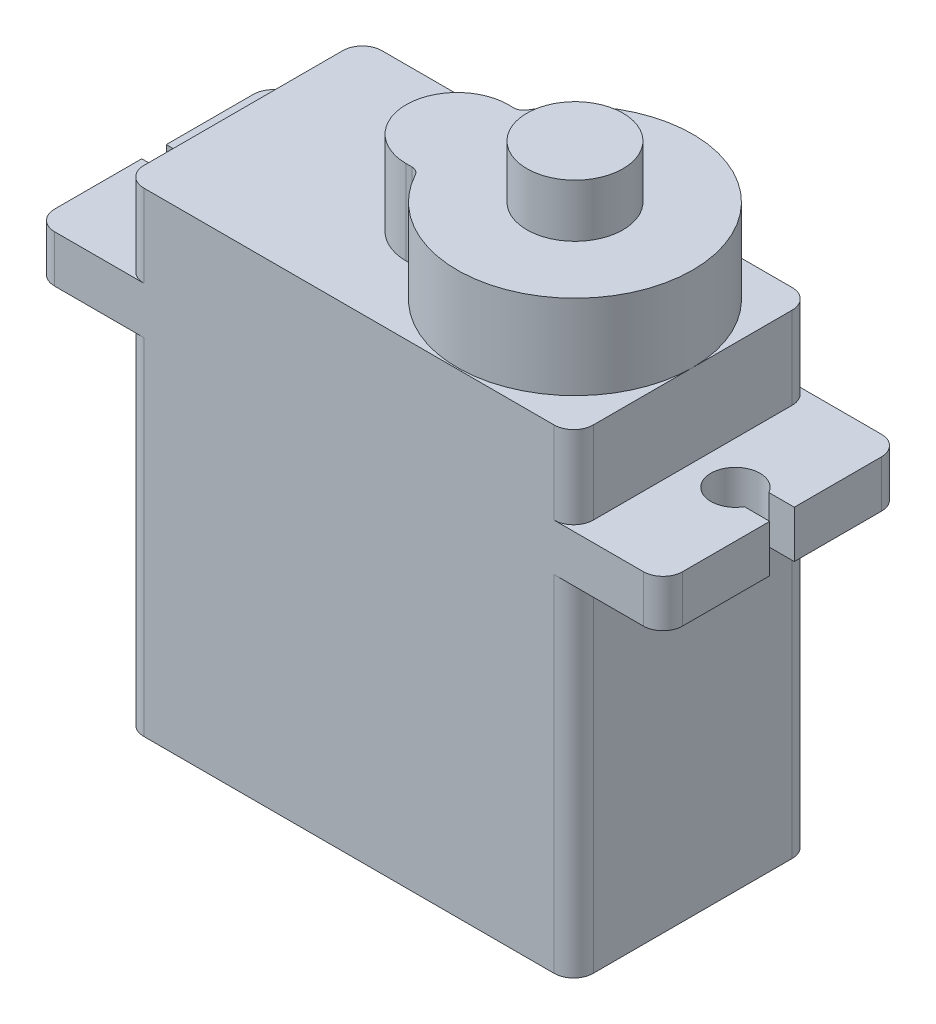
SolidWorks part; units mm, degrees
ref_plane "Plano frontal" through (0, 0, 0) normal (0, 0, 1) x (1, 0, 0)
ref_plane "Plano superior" through (0, 0, 0) normal (0, 1, 0) x (1, 0, 0)
ref_plane "Plano direito" through (0, 0, 0) normal (1, 0, 0) x (0, 0, -1)
sketch "Esboço2" plane through (0, 0, 0) normal (0, 1, 0) x (1, 0, 0)
  line L1 (11.45, 6.065) -> (-11.45, 6.065)
  line L2 (11.45, 6.065) -> (11.45, -6.065)
  line L3 (11.45, -6.065) -> (-11.45, -6.065)
  line L4 (-11.45, 6.065) -> (-11.45, -6.065)
  line L5 (11.45, 6.065) -> (-11.45, -6.065) construction
  line L6 (11.45, -6.065) -> (-11.45, 6.065) construction
  point P0 (0, 0)
  dimension "D1" = 22.9
  dimension "D2" = 12.13
extrude "Ressalto-extrusão1" add sketch "Esboço2" along normal blind 17.35
sketch "Esboço3" plane through (0, 17.35, 0) normal (0, 1, 0) x (1, 0, 0)
  line L1 (16, -6.065) -> (-16, -6.065)
  line L2 (16, -6.065) -> (16, 6.065)
  line L3 (16, 6.065) -> (-16, 6.065)
  line L4 (-16, -6.065) -> (-16, 6.065)
  line L5 (16, -6.065) -> (-16, 6.065) construction
  line L6 (16, 6.065) -> (-16, -6.065) construction
  line L7 (-11.45, -6.065) -> (11.45, -6.065) construction
  point P0 (0, 0)
  dimension "D1" = 32
  dimension "D2" = 0
extrude "Ressalto-extrusão2" add sketch "Esboço3" along normal blind 2.4
sketch "Esboço4" plane through (0, 19.75, 0) normal (0, 1, 0) x (1, 0, 0)
  line L1 (-11.45, -6.065) -> (11.45, -6.065)
  line L2 (-11.45, -6.065) -> (-11.45, 6.065)
  line L3 (-11.45, 6.065) -> (11.45, 6.065)
  line L4 (11.45, -6.065) -> (11.45, 6.065)
extrude "Ressalto-extrusão3" add sketch "Esboço4" along normal blind 4.45
sketch "Esboço5" plane through (0, 19.75, 0) normal (0, 1, 0) x (1, 0, 0)
  line L0 (0, -6.065) -> (0, 6.065) construction
  line L1 (-11.45, -6.065) -> (11.45, -6.065) construction
  line L2 (11.45, 6.065) -> (-11.45, 6.065) construction
  line L3 (-16, -0.625) -> (-16, 0.625)
  line L4 (-14.7075, 0.625) -> (-16, 0.625)
  line L5 (-14.7075, -0.625) -> (-16, -0.625)
  line L18 (14.7075, -0.625) -> (16, -0.625)
  line L19 (14.7075, 0.625) -> (16, 0.625)
  line L26 (16, -0.625) -> (16, 0.625)
  arc A0 (14.7075, 0.625) -> (14.7075, -0.625) centre (13.625, 0) ccw
  arc A1 (-14.7075, 0.625) -> (-14.7075, -0.625) centre (-13.625, 0) cw
  dimension "D2" = 2.5
extrude "Corte-extrusão1" cut sketch "Esboço5" against normal blind 2.4
sketch "Esboço6" plane through (0, 24.2, 0) normal (0, 1, 0) x (1, 0, 0)
  line L0 (11.25, -6) -> (11.25, 6) construction
  line L1 (-0.55, -2.6) -> (-0.2631, -2.6)
  line L3 (-0.55, 2.6) -> (-0.2631, 2.6)
  line L4 (11.45, -6.065) -> (11.45, 6.065) construction
  arc A0 (0.1763, -2.8615) -> (0.1763, 2.8615) centre (5.45, 0) ccw
  arc A1 (-0.55, 2.6) -> (-0.55, -2.6) centre (-0.55, 0) ccw
  arc A2 (0.1763, -2.8615) -> (-0.2631, -2.6) centre (-0.2631, -3.1) ccw
  arc A3 (0.1763, 2.8615) -> (-0.2631, 2.6) centre (-0.2631, 3.1) cw
  dimension "D2" = 0.5
  dimension "D1" = 12
  dimension "D3" = 6
extrude "Ressalto-extrusão4" add sketch "Esboço6" along normal blind 4.3
sketch "Esboço7" plane through (0, 28.5, 0) normal (0, 1, 0) x (1, 0, 0)
  circle A0 centre (5.45, 0) radius 2.45
  dimension "D1" = 4.9
extrude "Ressalto-extrusão5" add sketch "Esboço7" along normal blind 2.7
sketch "Esboço10" plane through (0, 28.5, 0) normal (0, 1, 0) x (1, 0, 0)
  line L1 (11.45, 6.065) -> (20.6404, 6.065)
  line L2 (11.45, 6.065) -> (11.45, -7.4178)
  line L3 (11.45, -7.4178) -> (20.6404, -7.4178)
  line L4 (20.6404, 6.065) -> (20.6404, -7.4178)
  line L5 (-11.45, 6.065) -> (-18.7442, 6.065)
  line L6 (-11.45, 6.065) -> (-11.45, -8.4924)
  line L7 (-11.45, -8.4924) -> (-18.7442, -8.4924)
  line L8 (-18.7442, 6.065) -> (-18.7442, -8.4924)
extrude "Corte-extrusão2" cut sketch "Esboço10" against normal blind 16 and the other way blind 1
ref_plane "Plano1" through (0, 17.6, 0) normal (0, 1, 0) x (1, 0, 0)
sketch "Esboço12" plane through (0, 17.6, 0) normal (0, 1, 0) x (1, 0, 0)
  line L1 (16, 0.625) -> (14.7075, 0.625)
  line L2 (16, 6.065) -> (11.45, 6.065)
  line L3 (16, 6.065) -> (16, 0.625)
  line L4 (16, -6.065) -> (11.45, -6.065)
  line L5 (11.45, 6.065) -> (11.45, -6.065)
  line L6 (16, -0.625) -> (14.7075, -0.625)
  line L7 (16, -0.625) -> (16, -6.065)
  line L8 (-16, -0.625) -> (-16, -6.065)
  line L9 (-16, -0.625) -> (-14.7075, -0.625)
  line L10 (-11.45, 6.065) -> (-11.45, -6.065)
  line L11 (-16, -6.065) -> (-11.45, -6.065)
  line L12 (-16, 6.065) -> (-16, 0.625)
  line L13 (-16, 6.065) -> (-11.45, 6.065)
  line L14 (-16, 0.625) -> (-14.7075, 0.625)
  arc A0 (14.7075, 0.625) -> (14.7075, -0.625) centre (13.625, 0) ccw
  arc A1 (-14.7075, 0.625) -> (-14.7075, -0.625) centre (-13.625, 0) cw
extrude "Ressalto-extrusão7" add sketch "Esboço12" along normal blind 2.4
fillet "Filete1" radius 1 10 edges at (-16, 18.8, -6.065) (-16, 18.8, 6.065) (16, 18.8, -6.065) (16, 18.8, 6.065) (-11.45, 8.8, 6.065) (-11.45, 22.1, 6.065) (11.45, 22.1, 6.065) (-11.45, 8.8, -6.065) (-11.45, 22.1, -6.065) (11.45, 22.1, -6.065)
